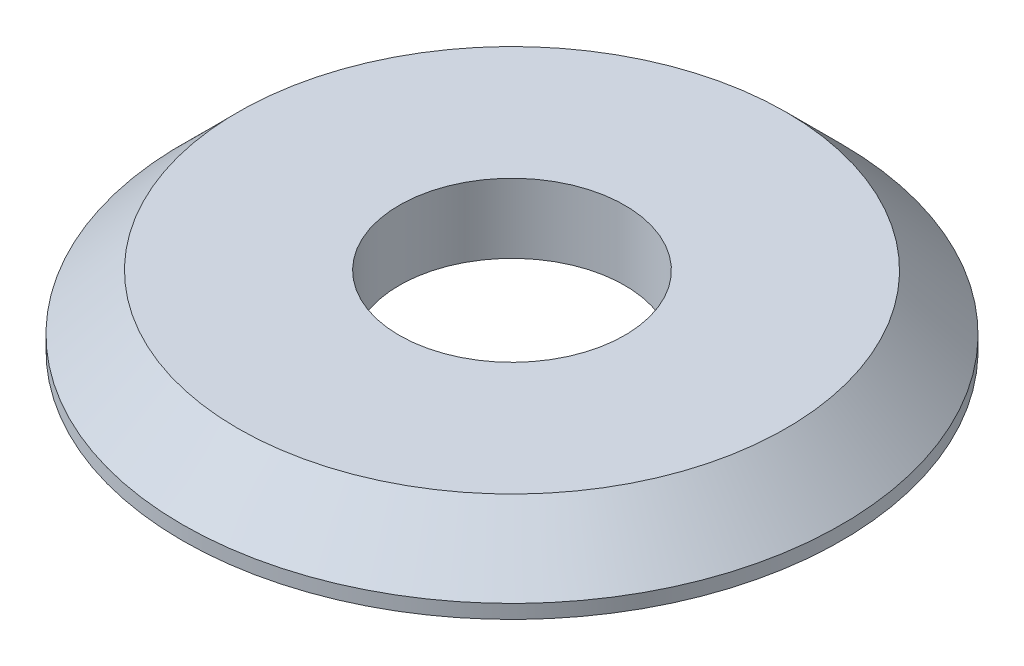
SolidWorks part; units mm, degrees
ref_plane "Ebene vorne" through (0, 0, 0) normal (0, 0, 1) x (1, 0, 0)
ref_plane "Ebene oben" through (0, 0, 0) normal (0, 1, 0) x (1, 0, 0)
ref_plane "Ebene rechts" through (0, 0, 0) normal (1, 0, 0) x (0, 0, -1)
sketch "Skizze1" plane through (0, 0, 0) normal (0, 1, 0) x (1, 0, 0)
  circle A0 centre (0, 0) radius 9.5
  circle A1 centre (0, 0) radius 3.25
  dimension "D1" = 19
  dimension "D2" = 6.5
extrude "Aufsatz-Linear austragen1" add sketch "Skizze1" along normal blind 2
chamfer "Fase1" distance 1.6 angle 45 1 edges at (0, 2, 9.5)
